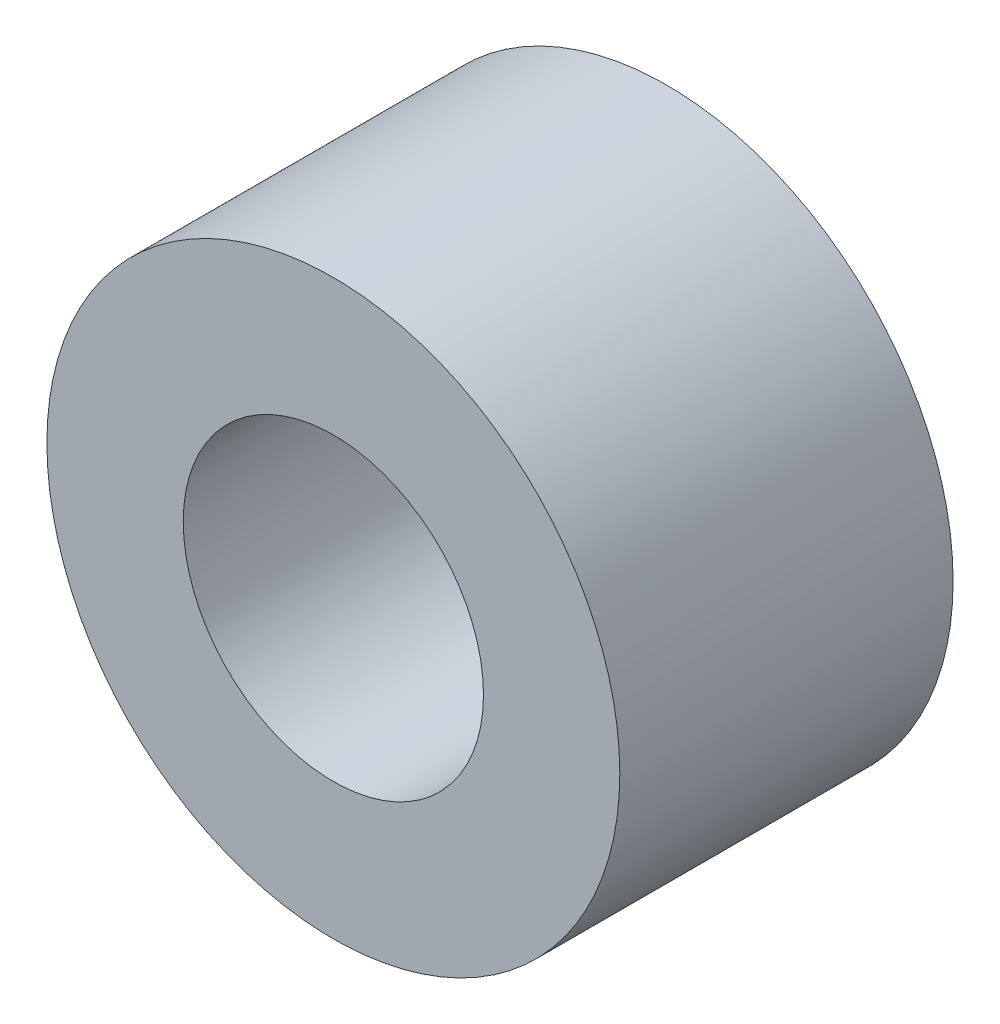
SolidWorks part; units mm, degrees
ref_plane "Plan de face" through (0, 0, 0) normal (1, 0, 0) x (0, 1, 0)
ref_plane "Plan de dessus" through (0, 0, 0) normal (0, 0, 1) x (0, 1, 0)
ref_plane "Plan de droite" through (0, 0, 0) normal (0, 1, 0) x (-1, 0, 0)
sketch "Esquisse1" plane through (0, 0, 0) normal (0, 0, 1) x (0, 1, 0)
  circle A0 centre (0, 0) radius 7.89
  circle A1 centre (0, 0) radius 4.135
  dimension "D1" = 8.27
  dimension "D2" = 15.78
extrude "Boss.-Extru.1" add sketch "Esquisse1" along normal blind 9.18
